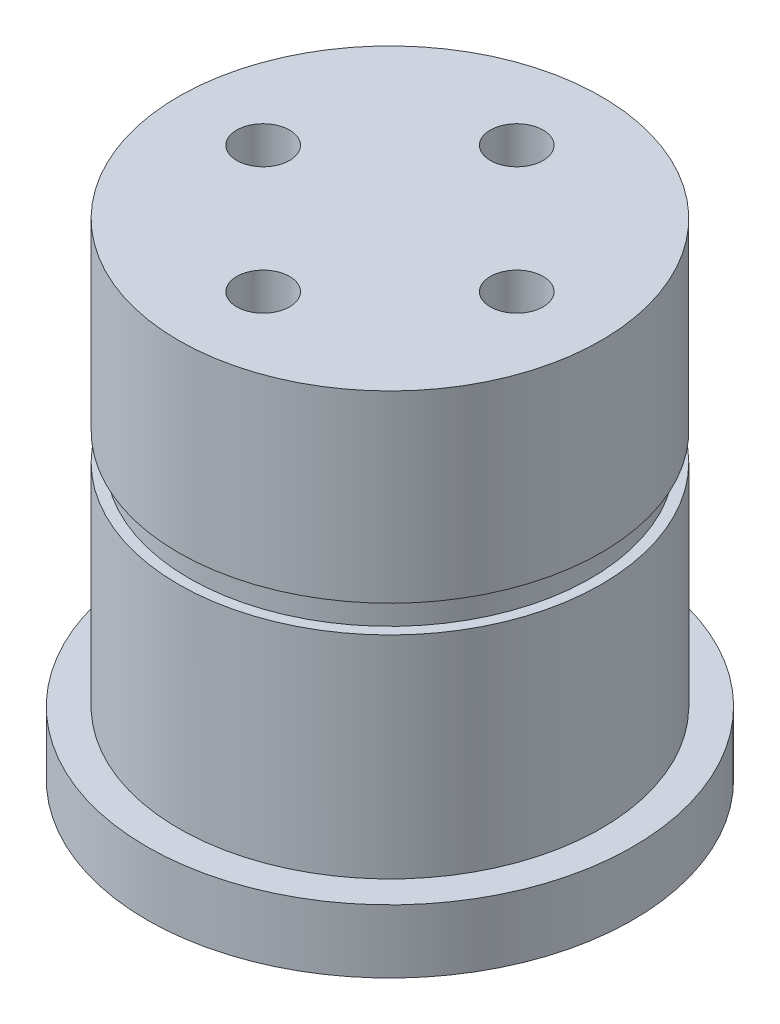
SolidWorks part; units mm, degrees
material "Сплав 2024"
ref_plane "Спереди" through (0, 0, 0) normal (0, 0, 1) x (1, 0, 0)
ref_plane "Сверху" through (0, 0, 0) normal (0, 1, 0) x (1, 0, 0)
ref_plane "Справа" through (0, 0, 0) normal (1, 0, 0) x (0, 0, -1)
sketch "Эскиз1" plane through (0, 0, 0) normal (0, 1, 0) x (1, 0, 0)
  circle A0 centre (0, 0) radius 10
  dimension "D1" = 20
extrude "Бобышка-Вытянуть1" add sketch "Эскиз1" along normal blind 23
sketch "Эскиз5" plane through (0, 0, 0) normal (0, -1, 0) x (1, 0, 0)
  line L0 (0, 10) -> (0, -10) construction
  line L1 (10, 0) -> (-10, 0) construction
  circle A1 centre (0, 0) radius 6 construction
  circle A2 centre (0, 0) radius 10 construction
  dimension "D1" = 12
hole_wizard "Отверстие обработанное метчиком M3x0.52" positions "Эскиз7" profile "Эскиз6" tap size "M3x0.5" standard "Ansi Metric"
sketch "Эскиз7" plane through (-4.8388, 23, -4.76) normal (0, -1, 0) x (-1, 0, 0)
  line L2 (-4.8388, -14.76) -> (-4.8388, 5.24) construction
  line L4 (-14.8388, -4.76) -> (5.1612, -4.76) construction
  circle A0 centre (-4.8388, -4.76) radius 6 construction
  point P0 (-4.8388, 1.24)
  point P6 (-10.8388, -4.76)
  point P10 (-4.8388, -10.76)
  point P12 (1.1612, -4.76)
sketch "Эскиз6" plane through (0, 23, -6) normal (1, 0, 0) x (0, 0, 1)
  line L0 (0, 0) -> (0, 9.2511)
  line L1 (0, 9.2511) -> (1.25, 8.5)
  line L2 (1.25, 8.5) -> (1.25, 0)
  line L5 (1.25, 0) -> (0, 0)
  line L10 (0, 9.2511) -> (-1.25, 8.5) construction
  line L11 (0, -6.35) -> (0, 107.95) construction
  dimension "Диаметр сверла" = 2.5
  dimension "Глубина сверла" = 8.5
  dimension "Угол заточки сверла" = 118
cosmetic thread "Отверстие резьбы1" parameters "D1"=6, "D2"=3
cosmetic thread "Отверстие резьбы2" parameters "D1"=6, "D2"=3
cosmetic thread "Отверстие резьбы3" parameters "D1"=6, "D2"=3
cosmetic thread "Отверстие резьбы4" parameters "D1"=6, "D2"=3
ref_plane "Плоскость2" through (0, 3, 0) normal (0, -1, 0) x (-1, 0, 0)
sketch "Эскиз10" plane through (0, 3, 0) normal (0, -1, 0) x (-1, 0, 0)
  circle A0 centre (0, 0) radius 11.5
  circle A2 centre (0, 0) radius 10
  circle A3 centre (0, 0) radius 10 construction
  dimension "D1" = 23
extrude "Бобышка-Вытянуть2" add sketch "Эскиз10" along normal up to surface (3 mm away) up to face at (0, 0, 10)
ref_plane "Плоскость1" through (0, 13, 0) normal (0, 1, 0) x (1, 0, 0)
sketch "Эскиз8" plane through (0, 13, 0) normal (0, 1, 0) x (1, 0, 0)
  circle A0 centre (0, 0) radius 10
  circle A1 centre (0, 0) radius 10 construction
  circle A3 centre (0, 0) radius 9.5
  dimension "D1" = 19
extrude "Вырез-Вытянуть1" cut sketch "Эскиз8" along normal blind 1.3
